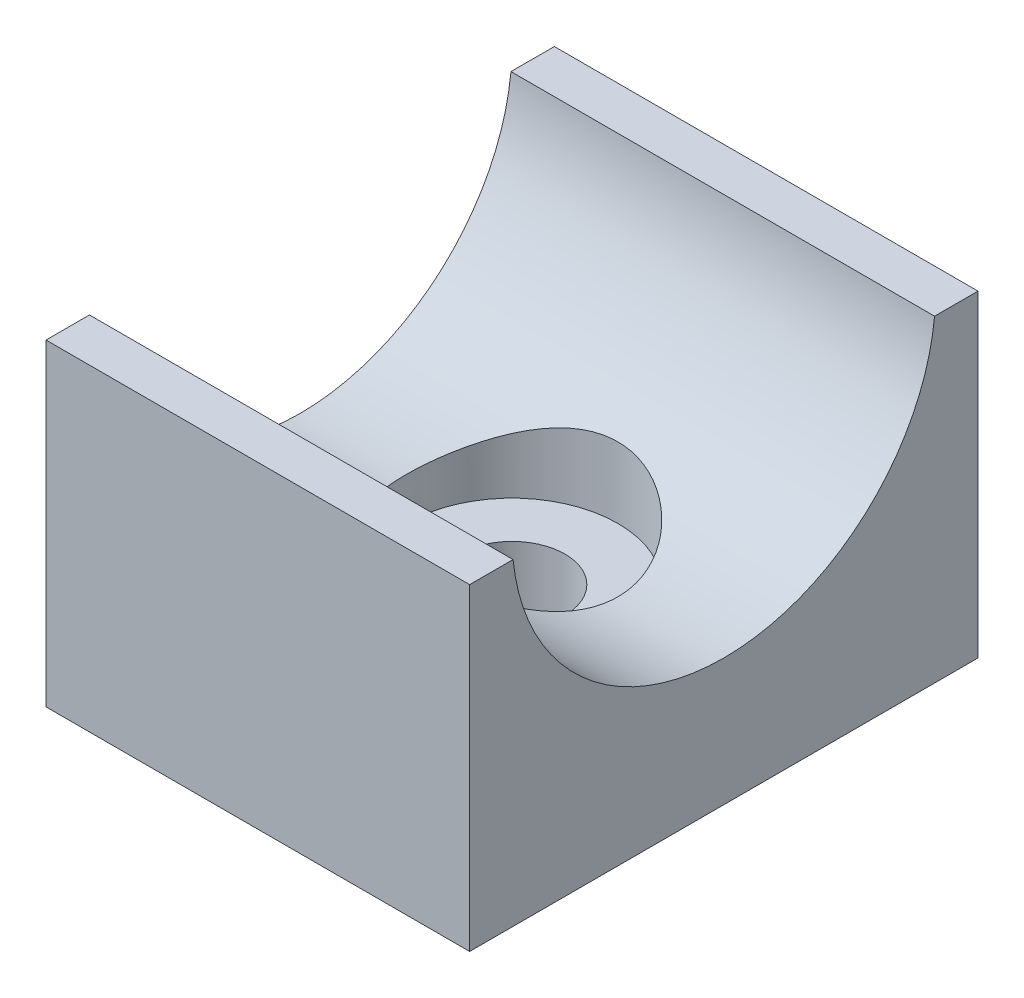
SolidWorks part; units mm, degrees
ref_plane "Front Plane" through (0, 0, 0) normal (0, 0, 1) x (1, 0, 0)
ref_plane "Top Plane" through (0, 0, 0) normal (0, 1, 0) x (1, 0, 0)
ref_plane "Right Plane" through (0, 0, 0) normal (1, 0, 0) x (0, 0, -1)
sketch "Sketch1" plane through (0, 0, 0) normal (1, 0, 0) x (0, 0, -1)
  line L0 (27.8763, 19.05) -> (30.48, 19.05)
  line L1 (0, 0) -> (30.48, 0)
  line L2 (0, 0) -> (0, 19.05)
  line L3 (0, 19.05) -> (2.6037, 19.05)
  line L4 (30.48, 0) -> (30.48, 19.05)
  arc A0 (2.6037, 19.05) -> (27.8763, 19.05) centre (15.24, 20.32) ccw
  dimension "D3" = 12.7
  dimension "D1" = 30.48
  dimension "D2" = 19.05
  dimension "D4" = 1.27
extrude "Boss-Extrude1" add sketch "Sketch1" along normal blind 25.4
sketch "Sketch2" plane through (0, 0, 0) normal (0, -1, 0) x (1, 0, 0)
  line L0 (12.7, 0) -> (12.7, -30.48) construction
  line L1 (25.4, 0) -> (0, 0) construction
  line L2 (25.4, -30.48) -> (0, -30.48) construction
  line L3 (25.4, -15.24) -> (0, -15.24) construction
  line L4 (25.4, 0) -> (25.4, -30.48) construction
  line L5 (0, 0) -> (0, -30.48) construction
  circle A0 centre (12.7, -15.24) radius 3.175
  point P14 (12.7, -15.24)
  dimension "D1" = 6.35
extrude "Cut-Extrude1" cut sketch "Sketch2" against normal through all and the other way through all
ref_plane "Plane1" through (0, 19.05, 0) normal (0, 1, 0) x (1, 0, 0)
sketch "Sketch3" plane through (0, 19.05, 0) normal (0, 1, 0) x (1, 0, 0)
  line L0 (0, 15.24) -> (25.4, 15.24) construction
  line L1 (0, 27.8763) -> (0, 2.6037) construction
  line L2 (25.4, 2.6037) -> (25.4, 27.8763) construction
  line L3 (12.7, 0) -> (12.7, 30.48) construction
  line L4 (25.4, 0) -> (0, 0) construction
  line L5 (25.4, 30.48) -> (0, 30.48) construction
  circle A0 centre (12.7, 15.24) radius 6.35
  dimension "D1" = 12.7
extrude "Cut-Extrude3" cut sketch "Sketch3" against normal offset from surface (13.97 mm away) 5.08 contours A0 up to face at (12.7, 0, -12.065)
